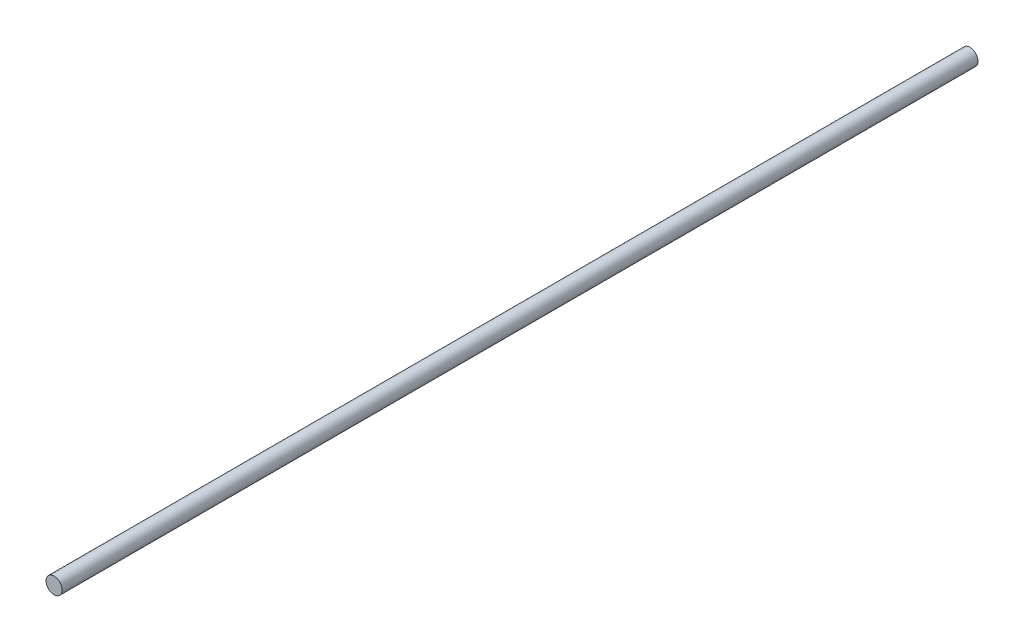
SolidWorks part; units mm, degrees
ref_plane "Alzado" through (0, 0, 0) normal (0, 0, 1) x (1, 0, 0)
ref_plane "Planta" through (0, 0, 0) normal (0, 1, 0) x (1, 0, 0)
ref_plane "Vista lateral" through (0, 0, 0) normal (1, 0, 0) x (0, 0, -1)
sketch "Croquis1" plane through (0, 0, 0) normal (0, 0, 1) x (1, 0, 0)
  circle A0 centre (0, 0) radius 3.175
  dimension "D1" = 6.35
extrude "Saliente-Extruir1" add sketch "Croquis1" along normal mid plane 360
